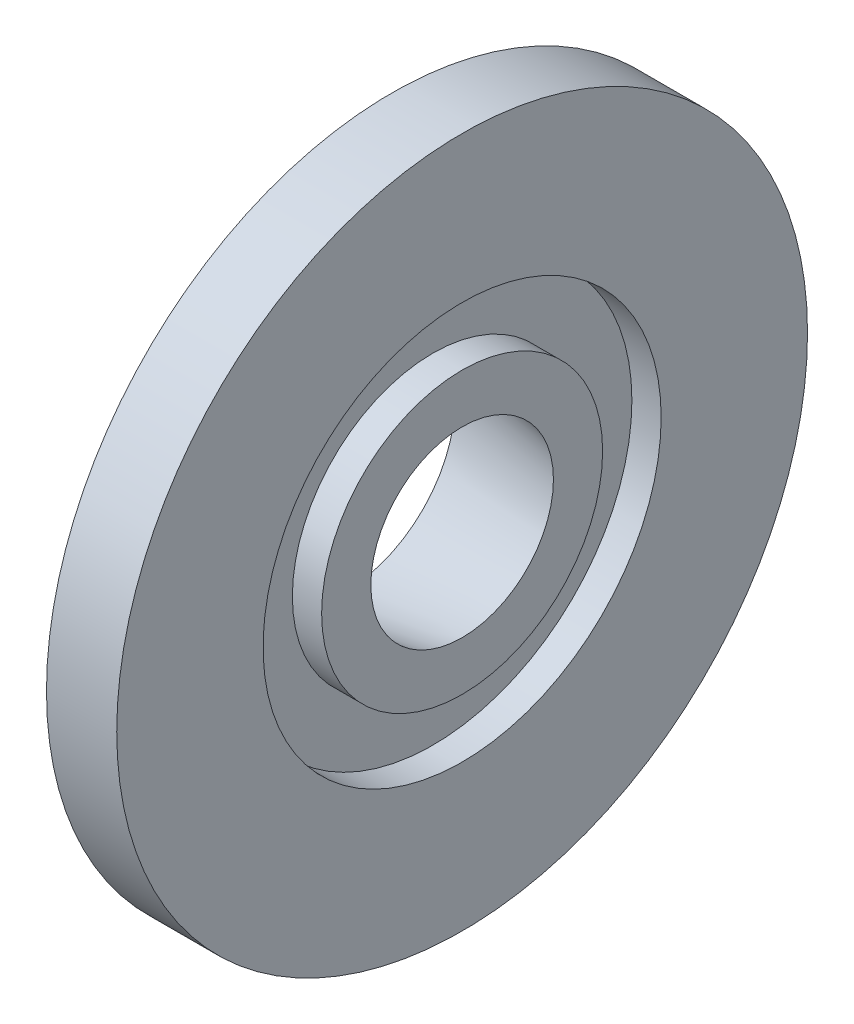
SolidWorks part; units mm, degrees
material "ASTM A36 Steel"
ref_plane "Front Plane" through (0, 0, 0) normal (0, 0, 1) x (1, 0, 0)
ref_plane "Top Plane" through (0, 0, 0) normal (0, 1, 0) x (1, 0, 0)
ref_plane "Right Plane" through (0, 0, 0) normal (1, 0, 0) x (0, 0, -1)
sketch "Sketch1" plane through (0, 0, 0) normal (0, 0, 1) x (1, 0, 0)
  line L0 (-2.54, 8.636) -> (-2.54, 14.986)
  line L1 (-5.588, 14.986) -> (-7.62, 7.4025)
  line L2 (-7.62, 7.4025) -> (-7.62, 0)
  line L3 (-3.81, 6.096) -> (-2.54, 6.096)
  line L4 (-2.54, 6.096) -> (-2.54, 0)
  line L5 (-7.62, 0) -> (-2.54, 0)
  line L6 (-3.81, 6.096) -> (-3.81, 8.636)
  line L7 (-3.81, 8.636) -> (-2.54, 8.636)
  line L8 (-12.5128, 0) -> (-40.2789, 0) construction
  line L9 (-2.54, 14.986) -> (-5.588, 14.986)
  dimension "D1" = 14.8049
  dimension "D2" = 2.54
  dimension "D3" = 17.272
  dimension "D4" = 2.54
  dimension "D5" = 1.27
  dimension "D6" = 15
  dimension "D7" = 3.048
  dimension "D8" = 5.08
  dimension "D9" = 29.972
revolve "Revolve1" add sketch "Sketch1" angle 360 about L8
sketch "Sketch2" plane through (0, 0, 0) normal (0, 0, 1) x (1, 0, 0)
  line L0 (-9.7285, 0) -> (0.0134, 0)
  line L1 (0.0134, 0) -> (0.0134, 3.5531)
  line L2 (0.0134, 3.5531) -> (-9.7285, 5.1114)
  line L3 (-9.7285, 5.1114) -> (-9.7285, 0)
  line L4 (-9.7285, 0) -> (-17.0533, 0) construction
  line L5 (-7.62, 7.4025) -> (-7.62, 0) construction
  point P3 (-7.62, 4.7741)
  dimension "D1" = 9.5482
revolve "Cut-Revolve1" cut sketch "Sketch2" angle 360 about L4
